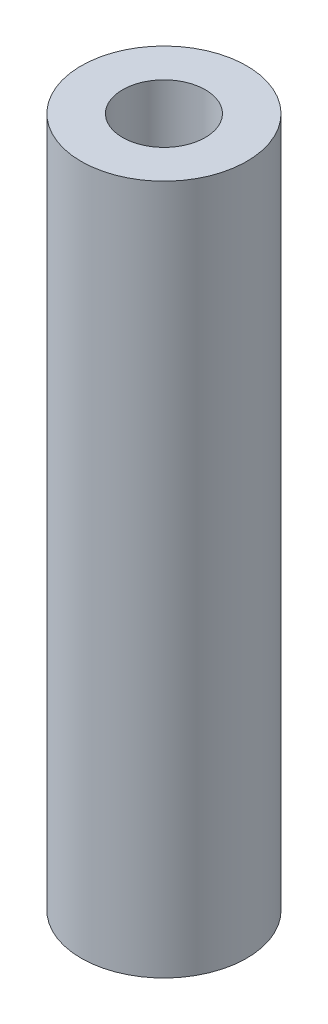
SolidWorks part; units mm, degrees
ref_plane "Front Plane" through (0, 0, 0) normal (0, 0, 1) x (1, 0, 0)
ref_plane "Top Plane" through (0, 0, 0) normal (0, 1, 0) x (1, 0, 0)
ref_plane "Right Plane" through (0, 0, 0) normal (1, 0, 0) x (0, 0, -1)
sketch "Sketch1" plane through (0, 0, 0) normal (0, 1, 0) x (1, 0, 0)
  circle A0 centre (0, 0) radius 1.5
  circle A1 centre (0, 0) radius 3
  dimension "D1" = 1.5
  dimension "D2" = 3
extrude "Boss-Extrude1" add sketch "Sketch1" along normal blind 25
